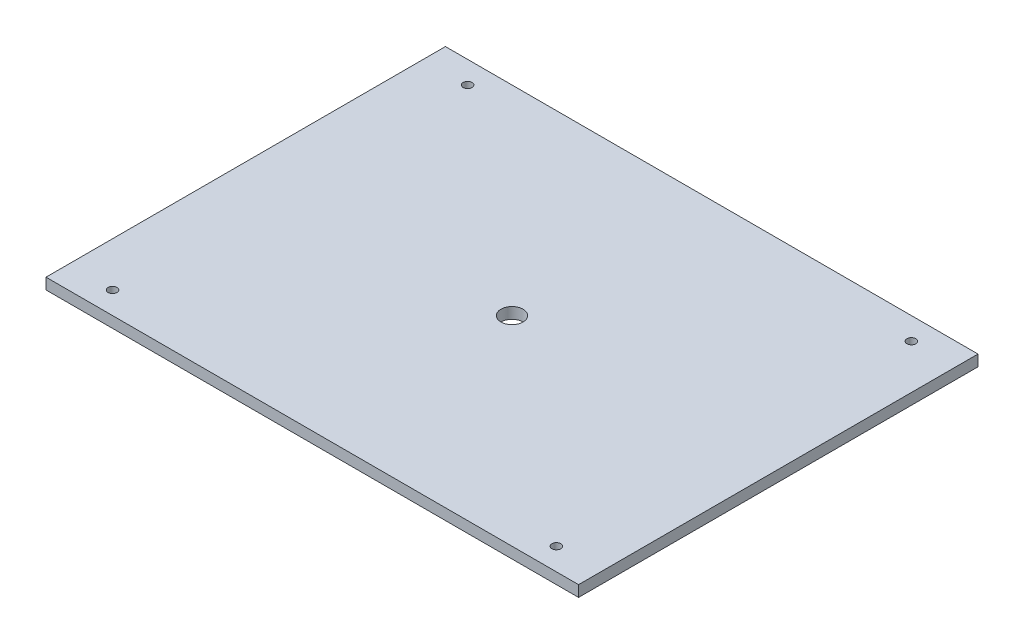
SolidWorks part; units mm, degrees
ref_plane "Front Plane" through (0, 0, 0) normal (0, 0, 1) x (1, 0, 0)
ref_plane "Top Plane" through (0, 0, 0) normal (0, 1, 0) x (1, 0, 0)
ref_plane "Right Plane" through (0, 0, 0) normal (1, 0, 0) x (0, 0, -1)
sketch "Sketch1" plane through (0, 0, 0) normal (0, 1, 0) x (1, 0, 0)
  line L0 (-100, -80) -> (100, -80) construction
  line L1 (-100, -80) -> (-100, 80) construction
  line L2 (-100, 80) -> (100, 80) construction
  line L3 (100, -80) -> (100, 80) construction
  line L4 (-100, -80) -> (100, 80) construction
  line L5 (-100, 80) -> (100, -80) construction
  line L7 (-120, -90) -> (120, -90)
  line L8 (-120, -90) -> (-120, 90)
  line L9 (-120, 90) -> (120, 90)
  line L10 (120, -90) -> (120, 90)
  line L11 (-120, -90) -> (120, 90) construction
  line L12 (-120, 90) -> (120, -90) construction
  circle A0 centre (-100, 80) radius 2
  circle A1 centre (100, 80) radius 2
  circle A2 centre (100, -80) radius 2
  circle A3 centre (-100, -80) radius 2
  circle A4 centre (0, 0) radius 5
  point P0 (0, 0)
  dimension "D3" = 4
  dimension "D4" = 10
  dimension "D1" = 200
  dimension "D2" = 160
  dimension "D5" = 10
  dimension "D6" = 20
extrude "Boss-Extrude1" add sketch "Sketch1" along normal blind 5
